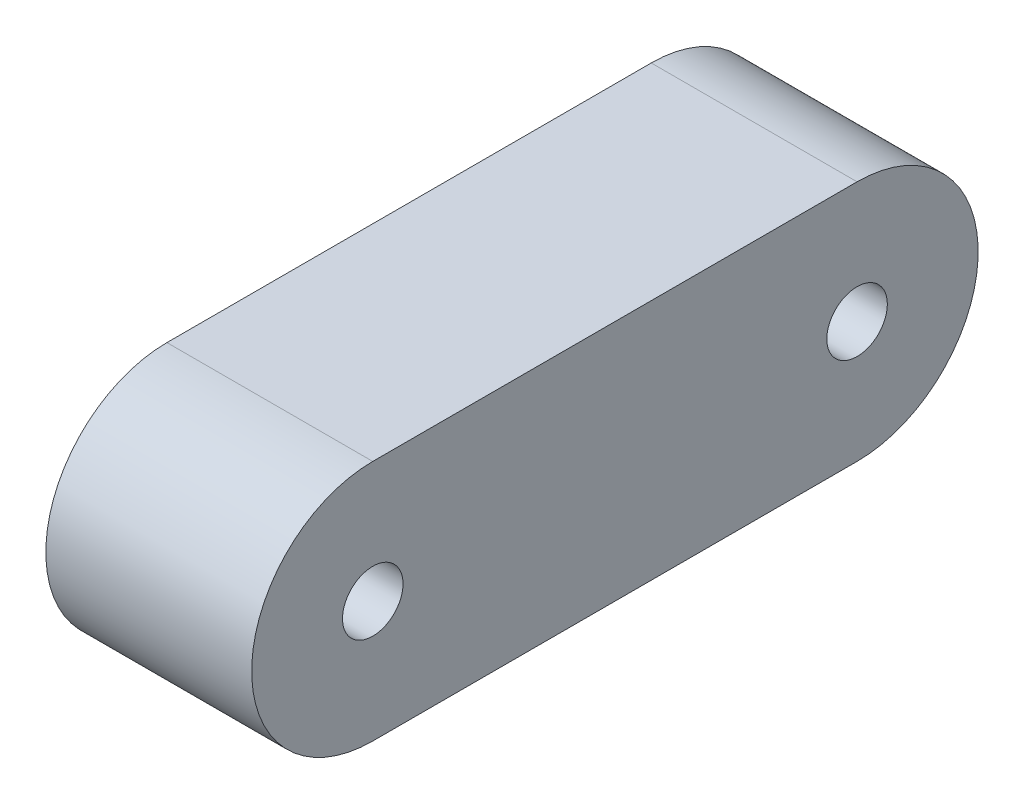
SolidWorks part; units mm, degrees
ref_plane "Alzado" through (0, 0, 0) normal (0, 0, 1) x (1, 0, 0)
ref_plane "Planta" through (0, 0, 0) normal (0, 1, 0) x (1, 0, 0)
ref_plane "Vista lateral" through (0, 0, 0) normal (1, 0, 0) x (0, 0, -1)
sketch "Croquis1" plane through (0, 0, 0) normal (1, 0, 0) x (0, 0, -1)
  line L0 (-20, 0) -> (20, 0) construction
  line L1 (-20, 10) -> (20, 10)
  line L2 (-20, -10) -> (20, -10)
  arc A0 (-20, 10) -> (-20, -10) centre (-20, 0) ccw
  arc A1 (20, -10) -> (20, 10) centre (20, 0) ccw
  circle A2 centre (-20, 0) radius 2.5
  circle A3 centre (20, 0) radius 2.5
  point P4 (0, 0)
  dimension "D1" = 20
  dimension "D3" = 5
  dimension "D2" = 40
extrude "Saliente-Extruir1" add sketch "Croquis1" along normal mid plane 17
